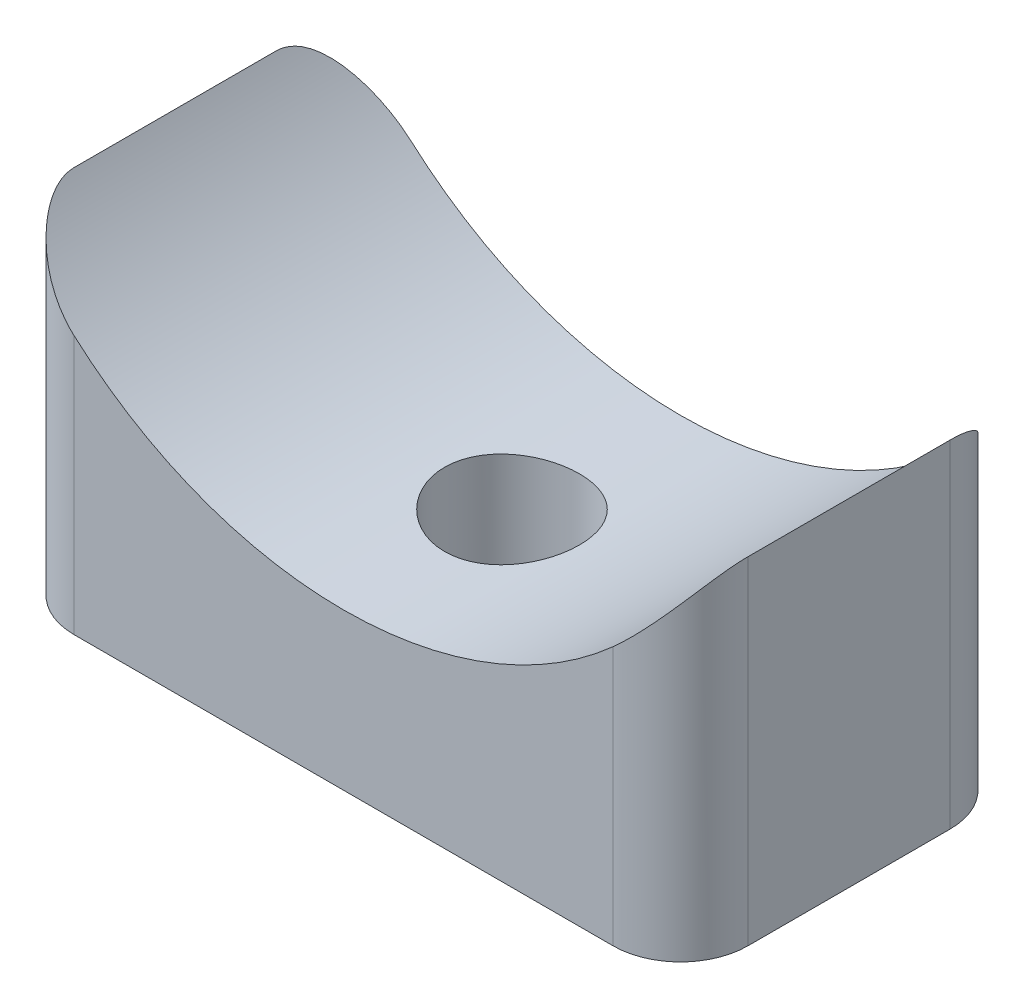
SolidWorks part; units mm, degrees
ref_plane "Front" through (0, 0, 0) normal (0, 0, 1) x (1, 0, 0)
ref_plane "Top" through (0, 0, 0) normal (0, 1, 0) x (1, 0, 0)
ref_plane "Right" through (0, 0, 0) normal (1, 0, 0) x (0, 0, -1)
sketch "草图1" plane through (0, 0, 0) normal (0, 0, 1) x (1, 0, 0)
  line L0 (0, 0) -> (20, 0)
  line L1 (20, 0) -> (20, 10)
  line L2 (0, 0) -> (0, 10)
  line L3 (10, 0) -> (10, 4) construction
  arc A1 (0, 10) -> (20, 10) centre (10, 16.6332) ccw
  dimension "D1" = 20
  dimension "D3" = 10
  dimension "D2" = 10
extrude "凸台-拉伸1" add sketch "草图1" along normal mid plane 10 contours A1 L1 L0 L2
sketch "草图2" plane through (0, 0, 0) normal (0, 1, 0) x (1, 0, 0)
  circle A0 centre (10, 0) radius 2
extrude "切除-拉伸1" cut sketch "草图2" along normal blind 15
fillet "圆角1" radius 2 4 edges at (20, 5, 5) (0, 5, -5) (0, 5, 5) (20, 5, -5)
